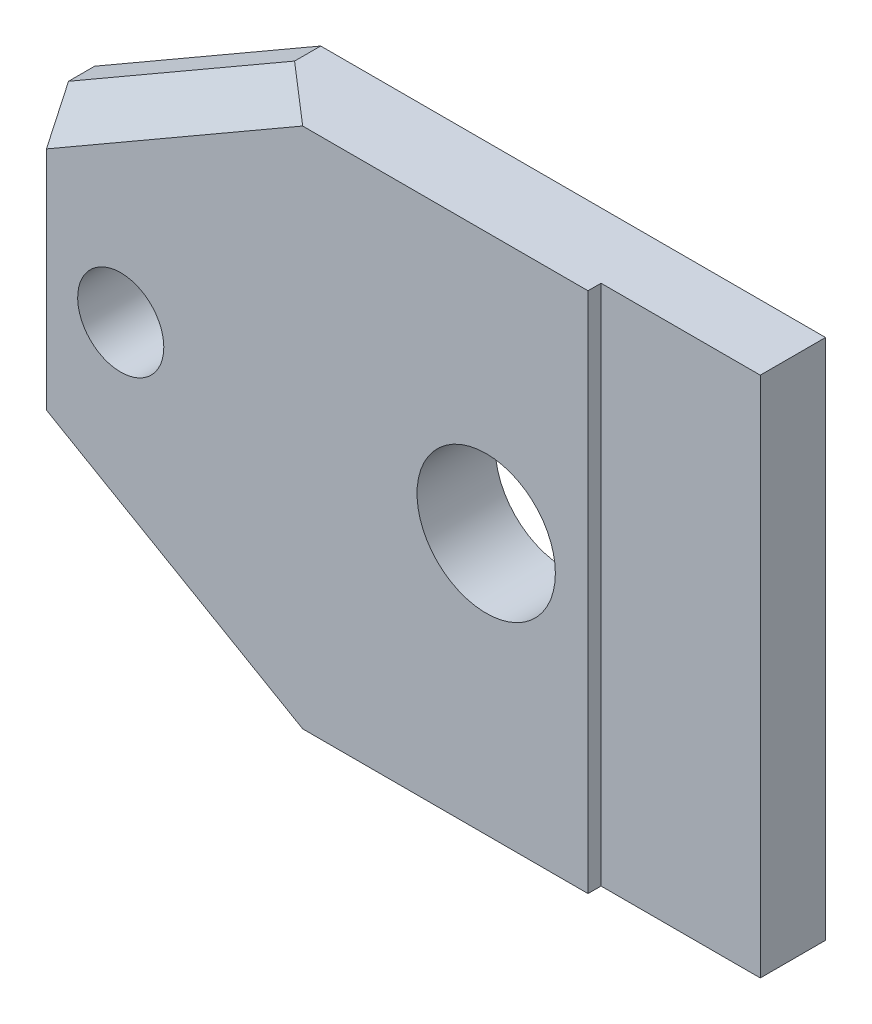
SolidWorks part; units mm, degrees
material "ABS"
ref_plane "Ebene vorne" through (0, 0, 0) normal (0, 0, 1) x (1, 0, 0)
ref_plane "Ebene oben" through (0, 0, 0) normal (0, 1, 0) x (1, 0, 0)
ref_plane "Ebene rechts" through (0, 0, 0) normal (1, 0, 0) x (0, 0, -1)
sketch "Skizze1" plane through (0, 0, 0) normal (0, 0, 1) x (1, 0, 0)
  line L0 (0, 0) -> (28, 0)
  line L1 (28, 0) -> (28, 2.5)
  line L2 (28, 2.5) -> (21.9, 2.5)
  line L3 (21.9, 2.5) -> (21.9, 3)
  line L4 (21.9, 3) -> (0, 3)
  line L5 (0, 3) -> (0, 0)
  line L6 (18, 3) -> (18, 0) construction
  line L7 (4, 3) -> (4, 0) construction
  line L8 (14, 3) -> (14, 0) construction
  line L9 (14, 0) -> (14, -6.2) construction
  line L10 (14, -6.2) -> (28, -6.2) construction
  line L11 (28, -6.2) -> (28, 0) construction
  line L12 (14, -6.2) -> (0, -6.2) construction
  line L13 (0, -6.2) -> (0, 0) construction
  line L14 (4, 0) -> (4, -6.2) construction
  circle A0 centre (4, 3) radius 1.65 construction
  circle A1 centre (18, 3) radius 2.65 construction
  dimension "D11" = 3.3
  dimension "D12" = 5.3
  dimension "D1" = 6.1
  dimension "D2" = 3
  dimension "D3" = 2.5
  dimension "D4" = 4
  dimension "D5" = 10
  dimension "D6" = 4
  dimension "D7" = 10
  dimension "D8" = 28
  dimension "D9" = 6.2
  dimension "D10" = 14
extrude "Aufsatz-Linear austragen1" add sketch "Skizze1" along normal blind 20
sketch "Skizze2" plane through (0, 0, 0) normal (0, -1, 0) x (1, 0, 0)
  line L0 (0, 10) -> (28, 10) construction
  line L1 (0, 20) -> (0, 0) construction
  line L2 (28, 20) -> (28, 0) construction
  circle A0 centre (4, 10) radius 1.65
  circle A1 centre (18, 10) radius 2.65
  dimension "D3" = 3.3
  dimension "D4" = 5.3
  dimension "D1" = 4
  dimension "D2" = 10
extrude "Schnitt-Linear austragen1" cut sketch "Skizze2" against normal up to surface (3 mm away) up to face at (10.95, 3, 10)
chamfer "Fase1" distance 5 angle 60 2 edges at (0, 1.5, 0) (0, 1.5, 20)
chamfer "Fase2" distance 2 angle 30 3 edges at (4.3301, 3, 17.5) (4.3301, 3, 2.5) (0, 3, 10)
move or copy body "Körper-Verschieben/Kopieren1" bodies to move or copy 102 copy no rotation origin (0, 1.5, 10) rotation axis (1, 0, 0) rotation angle 90
